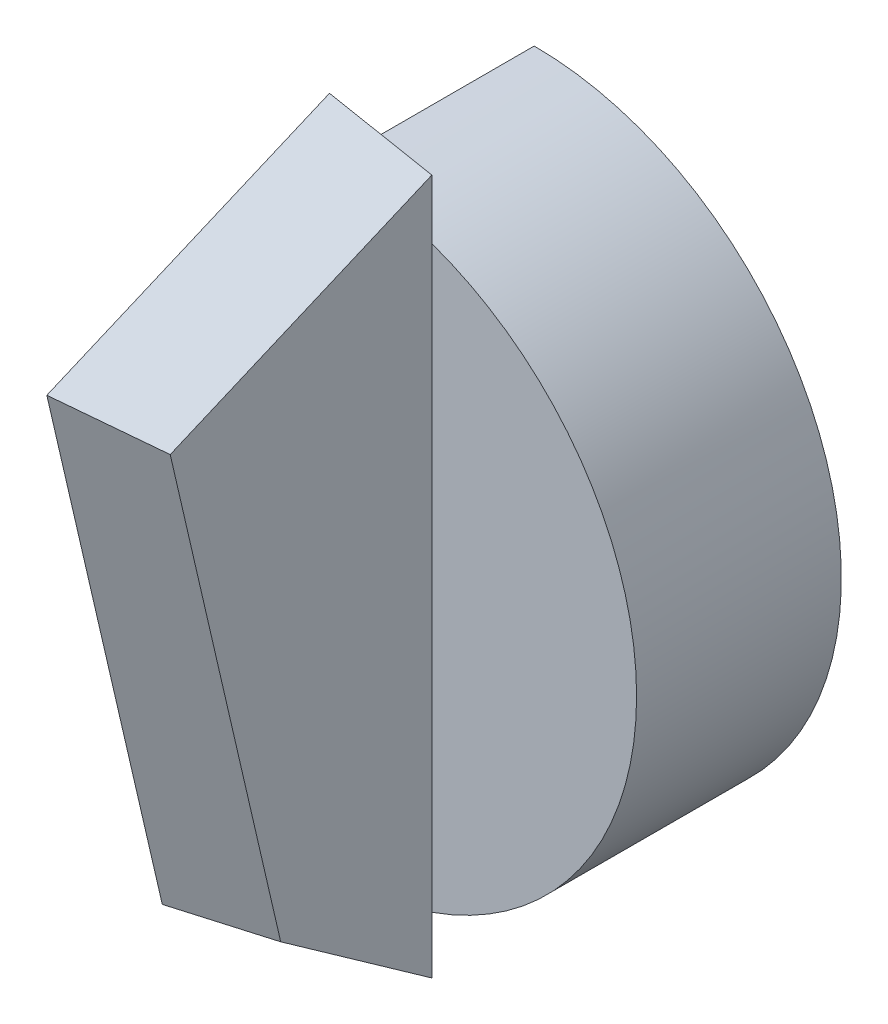
SolidWorks part; units mm, degrees
ref_plane "Front" through (0, 0, 0) normal (0, 0, 1) x (1, 0, 0)
ref_plane "Top" through (0, 0, 0) normal (0, 1, 0) x (1, 0, 0)
ref_plane "Right" through (0, 0, 0) normal (1, 0, 0) x (0, 0, -1)
other "Configuration Table"
sketch "Sketch1" plane through (0, 0, 0) normal (0, 0, 1) x (1, 0, 0)
  line L0 (0, 15) -> (0, -15)
  arc A0 (0, -15) -> (0, 15) centre (0, 0) ccw
  dimension "D1" = 15
extrude "Extrude1" add sketch "Sketch1" along normal blind 10
sketch "Sketch2" plane through (0, 0, 0) normal (1, 0, 0) x (0, 0, -1)
  line L0 (-10, 18) -> (-10, -18)
  line L1 (-10, -18) -> (-18.1643, -12.2255)
  line L2 (-18.1643, -12.2255) -> (-23.8038, 12.1301)
  line L3 (-23.8038, 12.1301) -> (-10, 18)
  line L4 (-10, 15) -> (-10, -15) construction
  dimension "D1" = 15
  dimension "D2" = 10
  dimension "D3" = 25
  dimension "D4" = 100
  dimension "D5" = 18
  dimension "D6" = 18
extrude "Extrude2" add sketch "Sketch2" along normal blind 5
draft "Draft1" type of draft neutral plane draft angle 10 neutral plane "Right" faces to draft 3 face at (2.5, -15.1128, 14.0821) face at (2.5, -0.0477, 20.984) face at (2.5, 15.0651, 16.9019) neutral plane through (0, 0, 0) neutral plane normal (1, 0, 0) parameters "D1"=10
